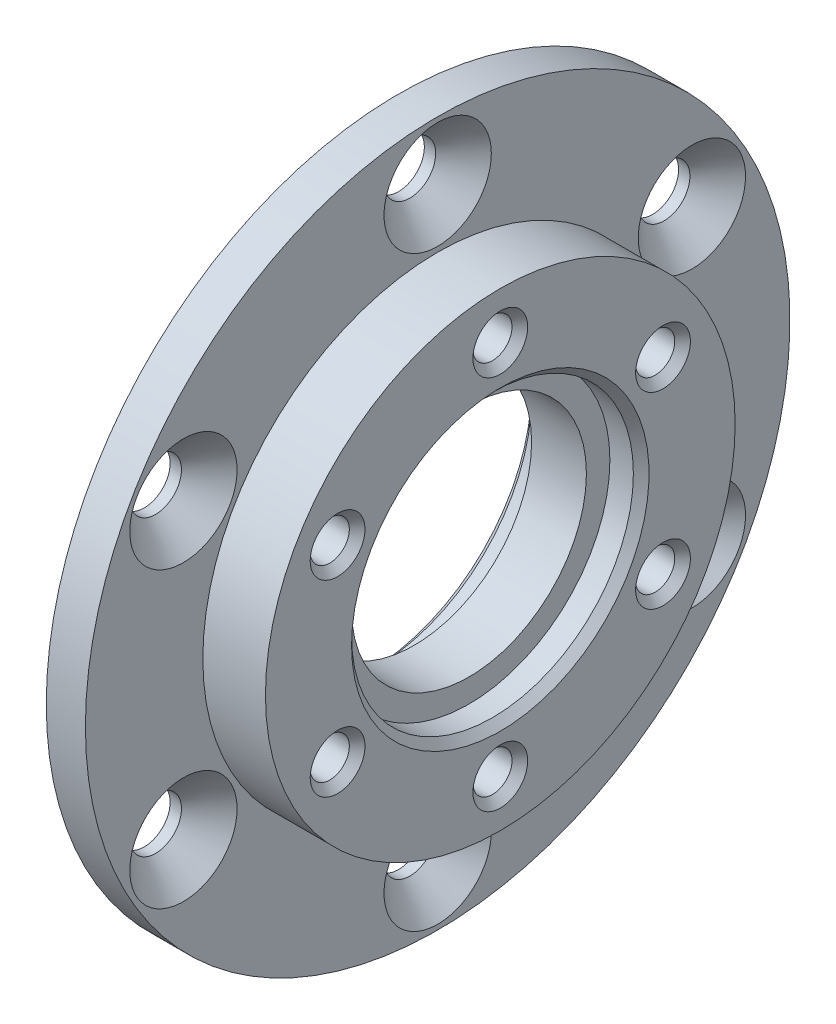
SolidWorks part; units mm, degrees
material "1.7033 (34Cr4)"
ref_plane "Спереди" through (0, 0, 0) normal (0, 0, 1) x (1, 0, 0)
ref_plane "Сверху" through (0, 0, 0) normal (0, 1, 0) x (1, 0, 0)
ref_plane "Справа" through (0, 0, 0) normal (1, 0, 0) x (0, 0, -1)
sketch "Эскиз1" plane through (0, 0, 0) normal (0, 0, 1) x (1, 0, 0)
  line L0 (0, 0) -> (-36109.6212, 0) construction
  line L1 (0, 20) -> (0, 27.5)
  line L2 (0, 27.5) -> (4, 27.5)
  line L3 (4, 27.5) -> (4, 45)
  line L4 (4, 45) -> (9, 45)
  line L5 (9, 45) -> (9, 30)
  line L6 (9, 30) -> (17, 30)
  line L7 (17, 30) -> (17, 15)
  line L8 (17, 15) -> (6, 15)
  line L9 (6, 15) -> (6, 20)
  line L10 (6, 20) -> (0, 20)
  dimension "D1" = 30
  dimension "D2" = 90
  dimension "D3" = 40
  dimension "D4" = 55
  dimension "D5" = 5
  dimension "D6" = 8
  dimension "D7" = 60
  dimension "D8" = 6
  dimension "D9" = 17
revolve "Повернуть1" add sketch "Эскиз1" angle 360 about L0
sketch "Эскиз4" plane through (17, 0, 0) normal (1, 0, 0) x (0, 0, -1)
  circle A0 centre (0, 0) radius 24 construction
  point P0 (0, 24)
  dimension "D1" = 48
hole_wizard "Отверстие обработанное метчиком M61" positions "Эскиз4" profile "Эскиз3" tap size "M6" standard "ISO"
sketch "Эскиз3" plane through (17, 24, 0) normal (0, 1, 0) x (0, 0, -1)
  line L0 (0, 0) -> (0, 10)
  line L1 (0, 10) -> (2.5, 8.4978)
  line L2 (2.5, 8.4978) -> (2.5, 0)
  line L5 (2.5, 0) -> (0, 0)
  line L10 (0, 10) -> (-2.5, 8.4978) construction
  line L11 (0, -6.35) -> (0, 107.95) construction
  dimension "Диаметр сверла" = 5
  dimension "Глубина сверла" = 10
  dimension "Угол заточки сверла" = 118
cosmetic thread "Отверстие резьбы1" parameters "D1"=6, "D2"=6
pattern_circular "Круговой массив1" count 6 over 360 about axis through (0, 0, 0) along (1, 0, 0) of "Отверстие обработанное метчиком M61"
cosmetic thread "Отверстие резьбы2" parameters "D1"=6, "D2"=6
cosmetic thread "Отверстие резьбы3" parameters "D1"=6, "D2"=6
cosmetic thread "Отверстие резьбы4" parameters "D1"=6, "D2"=6
cosmetic thread "Отверстие резьбы5" parameters "D1"=6, "D2"=6
cosmetic thread "Отверстие резьбы6" parameters "D1"=6, "D2"=6
sketch "Эскиз7" plane through (9, 0, 0) normal (1, 0, 0) x (0, 0, -1)
  line L0 (0, 0) -> (0, 50000) construction
  line L1 (0, 0) -> (0, 50000) construction
  circle A0 centre (0, 0) radius 37.5
  point P0 (0, 37.5)
  dimension "D1" = 75
  dimension "D2" = 0
hole_wizard "Зенковка для винта с потайной головкой и внутренним шестигранником M61" positions "Эскиз7" profile "Эскиз6" countersink size "M6" standard "DIN"
sketch "Эскиз6" plane through (9, 37.5, 0) normal (0, 1, 0) x (0, 0, -1)
  line L0 (0, 0) -> (0, 13)
  line L1 (0, 13) -> (3.3, 11.0172)
  line L2 (3.3, 11.0172) -> (3.3, 3.555)
  line L3 (3.3, 3.555) -> (6.855, 0)
  line L5 (6.855, 0) -> (0, 0)
  line L6 (-3.3, 3.555) -> (-6.855, 0) construction
  line L10 (0, 13) -> (-3.3, 11.0172) construction
  line L11 (0, -6.35) -> (0, 107.95) construction
  dimension "Диаметр отверстия" = 6.6
  dimension "Глубина отверстия" = 13
  dimension "Диаметр передней зенковки" = 13.71
  dimension "Угол передней зенковки" = 90
  dimension "Угол заточки сверла" = 118
pattern_circular "Круговой массив2" count 6 over 360 about axis through (0, 0, 0) along (1, 0, 0) of "Зенковка для винта с потайной головкой и внутренним шестигранником M61"
sketch "Эскиз8" plane through (17, 0, 0) normal (1, 0, 0) x (0, 0, -1)
  circle A2 centre (0, 0) radius 15 construction
  circle A3 centre (0, 0) radius 15
  circle A4 centre (0, 0) radius 18
  dimension "D2" = 36
extrude "Вырез-Вытянуть1" cut sketch "Эскиз8" against normal blind 4
chamfer "Фаска1" distance 1 angle 45 6 edges at (17, -24, -2.5) (17, -12, -23.2846) (17, -12, 18.2846) (17, 12, 18.2846) (17, 12, -23.2846) (17, 24, -2.5)
chamfer "Фаска2" distance 1 angle 45 3 edges at (0, 0, 20) (17, 0, -18) (0, 0, 27.5)
